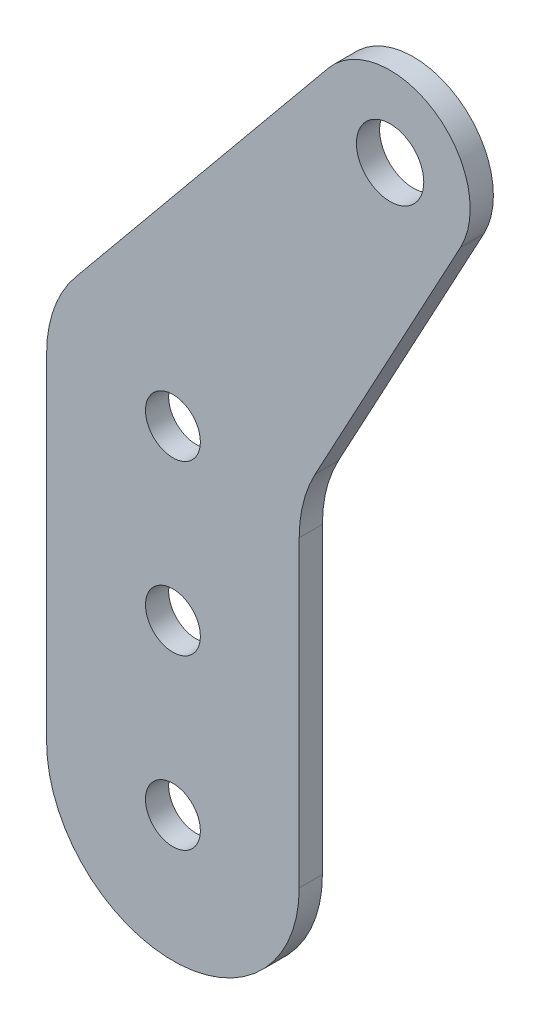
SolidWorks part; units mm, degrees
ref_plane "Front Plane" through (0, 0, 0) normal (0, 0, 1) x (1, 0, 0)
ref_plane "Top Plane" through (0, 0, 0) normal (0, 1, 0) x (1, 0, 0)
ref_plane "Right Plane" through (0, 0, 0) normal (1, 0, 0) x (0, 0, -1)
sketch "Sketch1" plane through (0, 0, 0) normal (0, 0, 1) x (1, 0, 0)
  line L0 (0, 44.2104) -> (0, -44.2104) construction
  line L1 (12.7, 58.5033) -> (12.7, -68.7049) construction
  line L2 (-12.7, 58.5033) -> (-12.7, -68.7049) construction
  line L3 (24.13, 57.707) -> (24.13, -3.288) construction
  line L4 (9.525, 25.4) -> (21.6943, 47.9295)
  line L5 (-7.3562, 31.4508) -> (11.7153, 54.6369)
  line L6 (-9.525, 25.4) -> (-9.525, 0)
  line L7 (9.525, 25.4) -> (9.525, 0)
  circle A0 centre (0, 0) radius 2.07
  circle A1 centre (0, 12.7) radius 2.07
  circle A2 centre (0, 25.4) radius 2.07
  circle A3 centre (16.38, 50.8) radius 2.54
  circle A4 centre (16.38, 50.8) radius 7.75 construction
  circle A5 centre (0, 0) radius 9.525
  circle A6 centre (0, 25.4) radius 9.525
  circle A7 centre (16.38, 50.8) radius 6.04
  dimension "D2" = 4.14
  dimension "D6" = 5.08
  dimension "D7" = 15.5
  dimension "D9" = 19.05
  dimension "D1" = 12.7
  dimension "D3" = 11.43
  dimension "D5" = 12.7
  dimension "D8" = 25.4
  dimension "D10" = 3.5
  dimension "D4" = 3
extrude "Boss-Extrude1" add sketch "Sketch1" along normal mid plane 1.75
fillet "Fillet2" radius 10 1 edges at (9.525, 25.4, 0)
